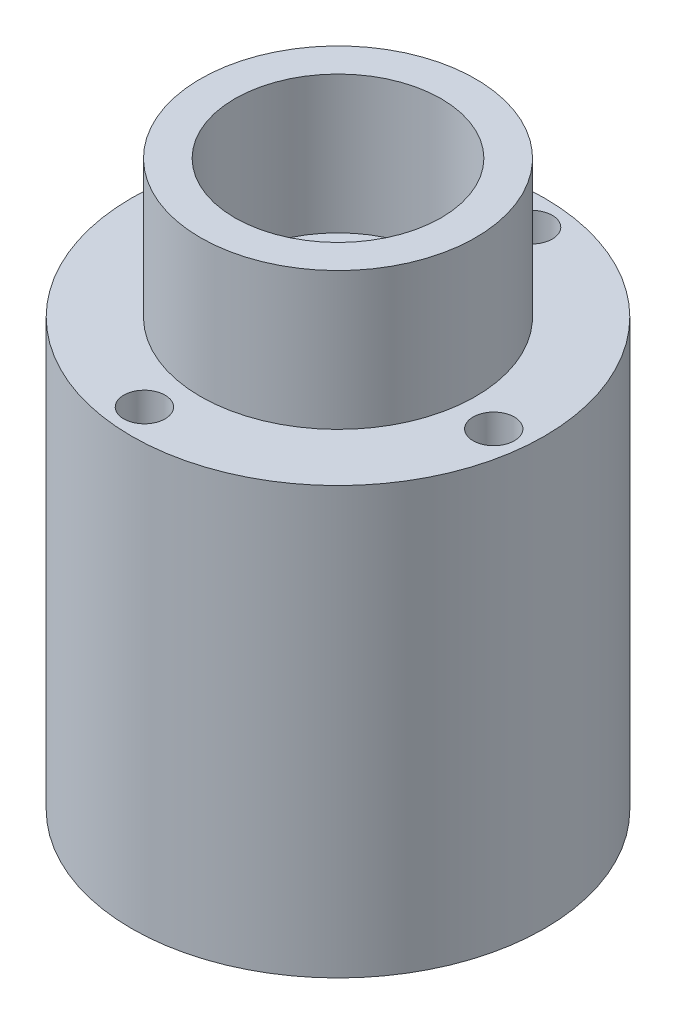
SolidWorks part; units mm, degrees
ref_plane "Front Plane" through (0, 0, 0) normal (0, 0, 1) x (1, 0, 0)
ref_plane "Top Plane" through (0, 0, 0) normal (0, 1, 0) x (1, 0, 0)
ref_plane "Right Plane" through (0, 0, 0) normal (1, 0, 0) x (0, 0, -1)
sketch "Sketch1" plane through (0, 0, 0) normal (0, 1, 0) x (1, 0, 0)
  circle A0 centre (0, 0) radius 15
  circle A1 centre (-12.6977, 1.3772) radius 1.5
  circle A2 centre (1.3772, 12.6977) radius 1.5
  circle A3 centre (12.6977, -1.3772) radius 1.5
  circle A4 centre (-1.3772, -12.6977) radius 1.5
  point P14 (0, 0)
  dimension "D1" = 4
  dimension "D2" = 30
extrude "Boss-Extrude1" add sketch "Sketch1" along normal blind 31
sketch "Sketch2" plane through (0, 31, 0) normal (0, 1, 0) x (1, 0, 0)
  circle A0 centre (0, 0) radius 10
  circle A1 centre (0, 0) radius 7.5
  dimension "D1" = 15
  dimension "D2" = 20
extrude "Boss-Extrude2" add sketch "Sketch2" along normal blind 10
